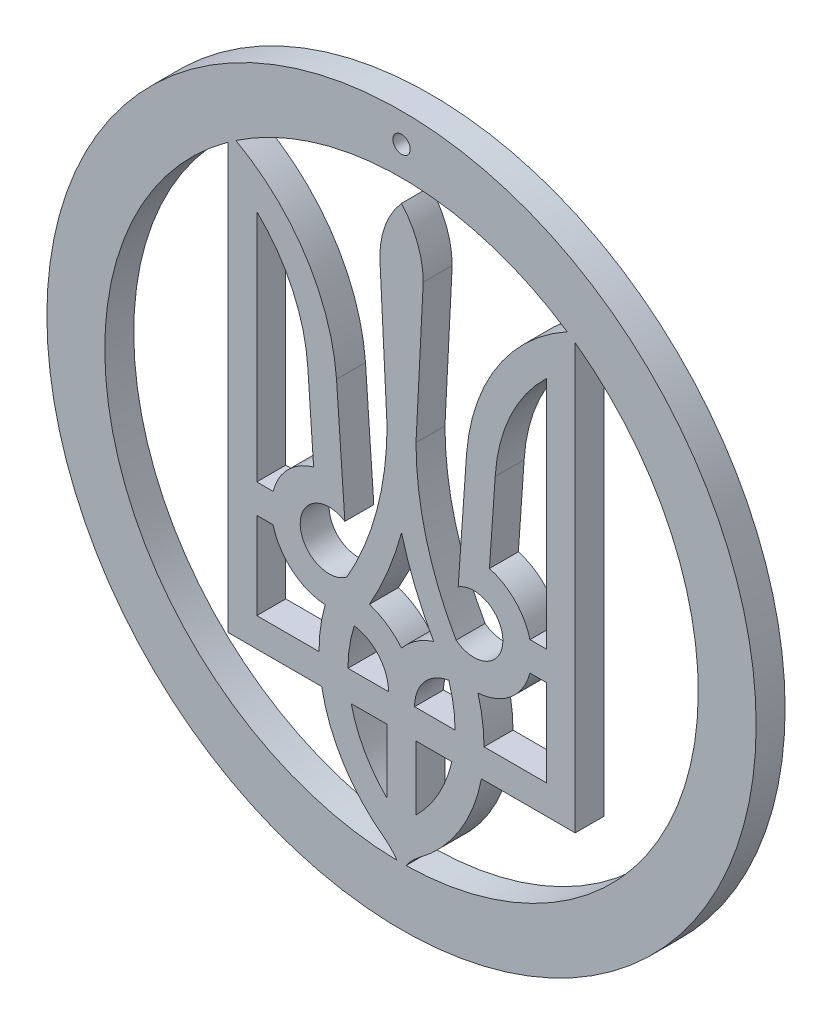
SolidWorks part; units mm, degrees
ref_plane "Спереди" through (0, 0, 0) normal (0, 0, 1) x (1, 0, 0)
ref_plane "Сверху" through (0, 0, 0) normal (0, 1, 0) x (1, 0, 0)
ref_plane "Справа" through (0, 0, 0) normal (1, 0, 0) x (0, 0, -1)
sketch "Эскиз1" plane through (0, 0, 0) normal (0, 0, 1) x (1, 0, 0)
  line L0 (0, 0) -> (-60, 0) construction
  line L1 (0, 0) -> (0, -45) construction
  line L2 (-27.5833, -45) -> (-60, -45)
  line L3 (-60, -45) -> (-60, 105)
  line L4 (-22.4495, 49.493) -> (-19.5761, 8.4012)
  line L5 (-22.38, 48.4989) -> (-20.3847, 19.9658) construction
  line L6 (0, 0) -> (15, 0) construction
  line L7 (0, -35) -> (26.5, -35) construction
  line L8 (0, -35) -> (-50, -35) construction
  line L9 (-28.5, -35) -> (-50, -35)
  line L10 (-50, -35) -> (-50, -5)
  line L11 (-50, 5) -> (-50, 85.9092)
  line L12 (-60, -45) -> (-90, -45) construction
  line L13 (-50, -35) -> (-50, 105) construction
  line L14 (-90, -45) -> (-90, 44.25) construction
  line L15 (0, 0) -> (0, 129.6666) construction
  line L16 (-60, 0) -> (-25, 0) construction
  line L17 (-44.3649, 5) -> (-50, 5)
  line L18 (-32.3556, 47.8014) -> (-30.3604, 19.2683)
  line L19 (-44.3649, -5) -> (-50, -5)
  line L20 (0, -45) -> (0, -95.3664) construction
  line L21 (-5, -67.1364) -> (-5, -45)
  line L22 (0, -45) -> (-60, -45) construction
  line L23 (-5, -45) -> (-17.3748, -45)
  line L24 (-18.5, -35) -> (-4.5, -35)
  line L25 (0, -45) -> (60, -45) construction
  line L26 (60, -45) -> (60, 93.5) construction
  line L27 (60, 93.5) -> (22.5, 93.5) construction
  line L28 (-90, 44.25) -> (-110, 44.25) construction
  line L29 (-7.5, 93.5) -> (0, 93.5) construction
  line L30 (-5, 44.25) -> (-7.5, 93.5)
  line L31 (0, -95.3664) -> (-18.004, -95.3664) construction
  line L32 (0, 113.3431) -> (0, -86.6569)
  arc A0 (-22.4495, 49.493) -> (-60, 105) centre (-90, 44.25) ccw
  arc A1 (-50, 85.9092) -> (-32.3556, 47.8014) centre (-90, 44.25) cw
  arc A2 (-44.3649, -5) -> (-26.4011, -19.9509) centre (-25, 0) ccw
  arc A3 (-19.5761, 8.4012) -> (-18.8639, -7.8961) centre (-25, 0) ccw
  arc A4 (-26.4011, -19.9509) -> (-28.5, -35) centre (26.5, -35) ccw
  arc A5 (-18.5, -35) -> (-16.3222, -21.1704) centre (26.5, -35) cw
  arc A6 (-27.5833, -45) -> (-5.9458, -79.4103) centre (26.5, -35) ccw
  arc A7 (-30.3604, 19.2683) -> (-44.3649, 5) centre (-25, 0) ccw
  arc A8 (-17.3748, -45) -> (-5, -67.1364) centre (26.5, -35) ccw
  arc A9 (-4.5, -35) -> (-16.3222, -21.1704) centre (-18.5, -35) ccw
  arc A10 (0, 113.3431) -> (-7.5, 93.5) centre (22.5, 93.5) ccw
  arc A11 (-18.8639, -7.8961) -> (-5, 44.25) centre (-110, 44.25) ccw
  arc A12 (0, -86.6569) -> (-5.9458, -79.4103) centre (-18.004, -95.3664) ccw
  arc A14 (0, -19.7111) -> (-11.0914, -12.1721) centre (-18.5, -35) ccw
  arc A16 (-11.0914, -12.1721) -> (0, 14.8157) centre (-110, 44.25) ccw
  point P3 (0, 5)
  point P7 (-87.4973, 5)
  point P8 (260.5938, -135.0208)
  point P9 (-87.4973, -5)
  point P26 (-19.6695, 9.7374)
  point P27 (-32.4251, 48.7954)
  point P28 (-29.6451, 9.0398)
  dimension "D9" = 135.5074
  dimension "D10" = 10
  dimension "D11" = 35
  dimension "D12" = 40
  dimension "D13" = 20
  dimension "D19" = 26.5
  dimension "D20" = 113.87
  dimension "D22" = 10
  dimension "D23" = 45
  dimension "D24" = 45
  dimension "D25" = 28
  dimension "D29" = 60
  dimension "D31" = 210
  dimension "D34" = 18.004
  dimension "D35" = 48
  dimension "D33" = 200
  dimension "D21" = 40
  dimension "D1" = 120
  dimension "D2" = 45
  dimension "D3" = 5
  dimension "D4" = 150
  dimension "D5" = 5
  dimension "D7" = 30
  dimension "D8" = 89.25
  dimension "D14" = 4
  dimension "D15" = 60.7207
  dimension "D17" = 21.5
  dimension "D18" = 15
  dimension "D26" = 60
  dimension "D27" = 138.5
  dimension "D28" = 37.5
  dimension "D30" = 20
  dimension "D32" = 7.5
  dimension "D36" = 200
  dimension "D6" = 10
  dimension "D16" = 10
extrude "Бобышка-Вытянуть1" add sketch "Эскиз1" along normal blind 10 contours A14 A16 L32 A10 L30 A11 A3 L4 A0 L3 L2 A6 A12 L18 A7 L17 L11 A1 A2 A4 L9 L10 L19 A8 L23 L21 A9 L24 A5
mirror "Зеркальное отражение1" about plane through (0, 0, 0) normal (1, 0, 0) of "Бобышка-Вытянуть1"
sketch "Эскиз3" plane through (0, 0, 0) normal (0, 0, 1) x (1, 0, 0)
  line L0 (0, 0) -> (0, 18.5) construction
  line L1 (0, 121) -> (0, 141) construction
  circle A0 centre (0, 18.5) radius 102.5
  circle A1 centre (0, 18.5) radius 122.5
  circle A2 centre (0, 131) radius 3
  dimension "D1" = 20
  dimension "D2" = 18.5
  dimension "D3" = 205
  dimension "D4" = 6
extrude "Бобышка-Вытянуть2" add sketch "Эскиз3" along normal blind 10 contours A1
